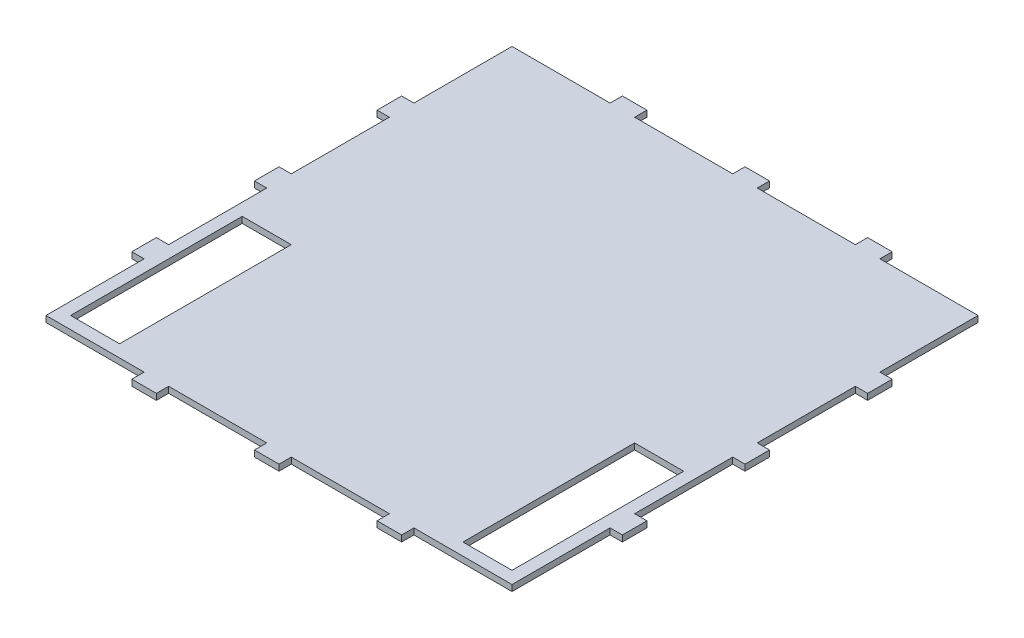
SolidWorks part; units mm, degrees
material "6061 Alloy"
ref_plane "Front Plane" through (0, 0, 0) normal (0, 0, 1) x (1, 0, 0)
ref_plane "Top Plane" through (0, 0, 0) normal (0, 1, 0) x (1, 0, 0)
ref_plane "Right Plane" through (0, 0, 0) normal (1, 0, 0) x (0, 0, -1)
sketch "Sketch1" plane through (0, 0, 0) normal (0, 1, 0) x (1, 0, 0)
  line L0 (0, 63.5) -> (0, -63.5) construction
  line L1 (63.5, -63.5) -> (-63.5, -63.5) construction
  line L2 (63.5, -63.5) -> (63.5, 63.5) construction
  line L3 (63.5, 63.5) -> (-63.5, 63.5) construction
  line L4 (-63.5, -63.5) -> (-63.5, 63.5) construction
  line L5 (63.5, -63.5) -> (-63.5, 63.5) construction
  line L6 (63.5, 63.5) -> (-63.5, -63.5) construction
  line L7 (-63.5, 0) -> (63.5, 0) construction
  line L8 (3.175, 63.5) -> (-3.175, 63.5)
  line L9 (-3.175, 63.5) -> (-3.175, 60.325)
  line L10 (-3.175, 60.325) -> (-28.575, 60.325)
  line L11 (-28.575, 60.325) -> (-28.575, 63.5)
  line L12 (-28.575, 63.5) -> (-34.925, 63.5)
  line L13 (-34.925, 63.5) -> (-34.925, 60.325)
  line L14 (-34.925, 60.325) -> (-60.325, 60.325)
  line L15 (-60.325, 60.325) -> (-60.325, 34.925)
  line L16 (-60.325, 34.925) -> (-63.5, 34.925)
  line L17 (-63.5, 34.925) -> (-63.5, 28.575)
  line L18 (-63.5, 28.575) -> (-60.325, 28.575)
  line L19 (-60.325, 28.575) -> (-60.325, 3.175)
  line L20 (-60.325, 3.175) -> (-63.5, 3.175)
  line L21 (-63.5, 3.175) -> (-63.5, -3.175)
  line L22 (-63.5, -28.575) -> (-60.325, -28.575)
  line L23 (-63.5, -34.925) -> (-63.5, -28.575)
  line L24 (-60.325, -34.925) -> (-63.5, -34.925)
  line L25 (-60.325, -60.325) -> (-60.325, -34.925)
  line L26 (-34.925, -60.325) -> (-60.325, -60.325)
  line L27 (-34.925, -63.5) -> (-34.925, -60.325)
  line L28 (-28.575, -63.5) -> (-34.925, -63.5)
  line L29 (-28.575, -60.325) -> (-28.575, -63.5)
  line L30 (-3.175, -60.325) -> (-28.575, -60.325)
  line L31 (-3.175, -63.5) -> (-3.175, -60.325)
  line L32 (3.175, -63.5) -> (-3.175, -63.5)
  line L33 (-60.325, -28.575) -> (-60.325, -3.175)
  line L34 (-60.325, -3.175) -> (-63.5, -3.175)
  line L35 (63.5, -63.5) -> (63.5, 63.5) construction
  line L36 (60.325, -3.175) -> (63.5, -3.175)
  line L37 (60.325, -28.575) -> (60.325, -3.175)
  line L38 (3.175, -63.5) -> (3.175, -60.325)
  line L39 (3.175, -60.325) -> (28.575, -60.325)
  line L40 (28.575, -60.325) -> (28.575, -63.5)
  line L41 (28.575, -63.5) -> (34.925, -63.5)
  line L42 (34.925, -63.5) -> (34.925, -60.325)
  line L43 (34.925, -60.325) -> (60.325, -60.325)
  line L44 (60.325, -60.325) -> (60.325, -34.925)
  line L45 (60.325, -34.925) -> (63.5, -34.925)
  line L46 (63.5, -34.925) -> (63.5, -28.575)
  line L47 (63.5, -28.575) -> (60.325, -28.575)
  line L48 (63.5, -3.175) -> (63.5, 3.175)
  line L49 (60.325, 3.175) -> (63.5, 3.175)
  line L50 (60.325, 28.575) -> (60.325, 3.175)
  line L51 (63.5, 28.575) -> (60.325, 28.575)
  line L52 (63.5, 34.925) -> (63.5, 28.575)
  line L53 (60.325, 34.925) -> (63.5, 34.925)
  line L54 (60.325, 60.325) -> (60.325, 34.925)
  line L55 (34.925, 60.325) -> (60.325, 60.325)
  line L56 (34.925, 63.5) -> (34.925, 60.325)
  line L57 (28.575, 63.5) -> (34.925, 63.5)
  line L58 (28.575, 60.325) -> (28.575, 63.5)
  line L59 (3.175, 60.325) -> (28.575, 60.325)
  line L60 (3.175, 63.5) -> (3.175, 60.325)
  line L61 (44.45, -57.15) -> (44.45, -12.7)
  line L62 (-57.15, -57.15) -> (-44.45, -57.15)
  line L63 (-57.15, -57.15) -> (-57.15, -12.7)
  line L64 (-57.15, -12.7) -> (-44.45, -12.7)
  line L65 (-44.45, -57.15) -> (-44.45, -12.7)
  line L66 (57.15, -57.15) -> (44.45, -57.15)
  line L67 (57.15, -57.15) -> (57.15, -12.7)
  line L68 (57.15, -12.7) -> (44.45, -12.7)
  point P0 (0, 0)
  dimension "D1" = 127
  dimension "D2" = 6.35
  dimension "D3" = 3.175
  dimension "D4" = 3.175
  dimension "D5" = 12.7
  dimension "D6" = 44.45
  dimension "D7" = 6.35
extrude "Boss-Extrude1" add sketch "Sketch1" along normal blind 1.5875
